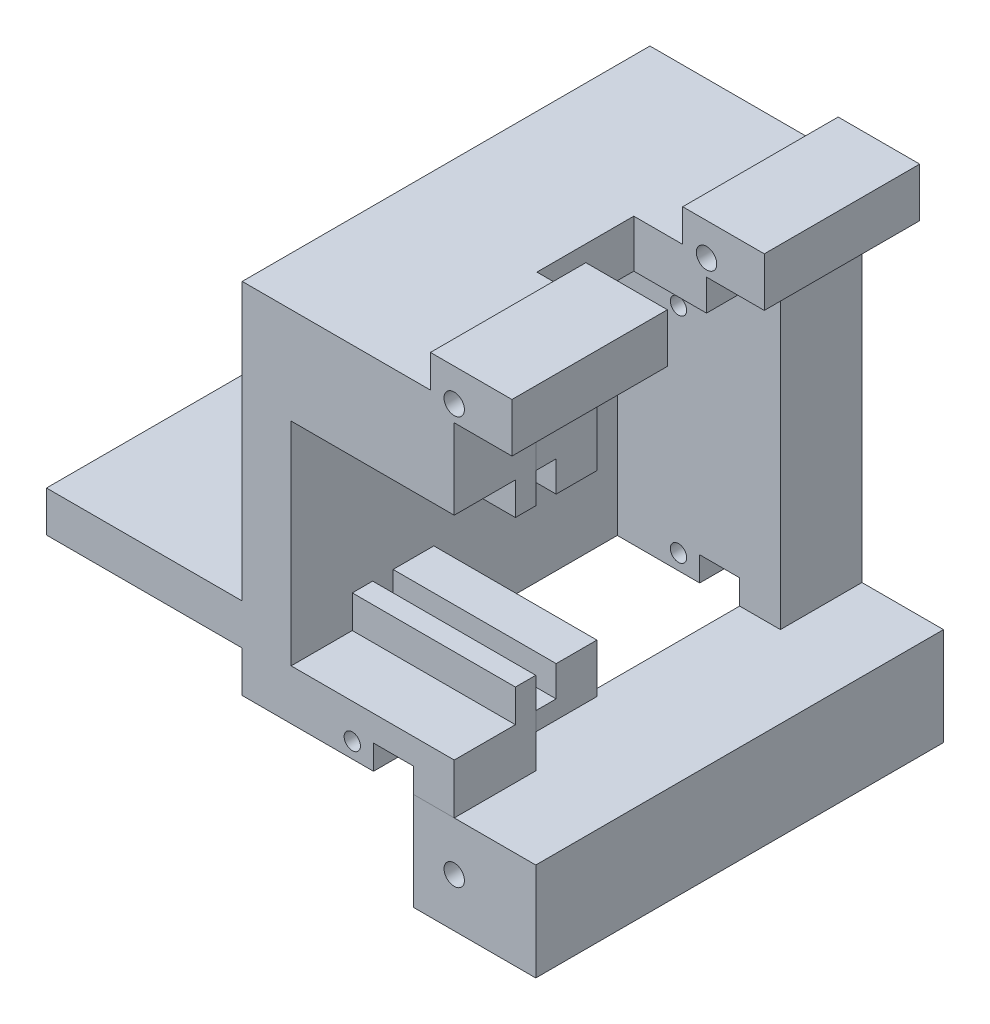
SolidWorks part; units mm, degrees
material "ABS"
ref_plane "Front Plane" through (0, 0, 0) normal (0, 0, 1) x (1, 0, 0)
ref_plane "Top Plane" through (0, 0, 0) normal (0, 1, 0) x (1, 0, 0)
ref_plane "Right Plane" through (0, 0, 0) normal (1, 0, 0) x (0, 0, -1)
sketch "Sketch8" plane through (0, 0, 0) normal (0, 0, 1) x (1, 0, 0)
  line L0 (0, 0) -> (0, 48.6918)
  line L1 (0, 48.6918) -> (-33.02, 48.6918)
  line L2 (-33.02, 48.6918) -> (-33.02, 5.588)
  line L3 (-33.02, 5.588) -> (-63.5, 5.588)
  line L4 (-63.5, 5.588) -> (-63.5, -0.762)
  line L5 (-63.5, -0.762) -> (-33.02, -0.762)
  line L6 (-33.02, -0.762) -> (-33.02, -9.525)
  line L8 (-33.02, -9.525) -> (-9.525, -9.525)
  line L11 (0, 0) -> (0, -9.525)
  line L12 (0, -9.525) -> (-9.525, -9.525)
  line L13 (-15.875, -4.7625) -> (-15.875, 28.5877) construction
  circle A0 centre (-15.875, 28.5877) radius 1.27
  circle A1 centre (-15.875, -4.7625) radius 1.27
  dimension "D7" = 2.54
  dimension "D8" = 15.875
  dimension "D1" = 30.48
  dimension "D2" = 33.02
  dimension "D3" = 48.6918
  dimension "D4" = 43.1038
  dimension "D5" = 6.35
  dimension "D6" = 23.495
extrude "Boss-Extrude3" add sketch "Sketch8" along normal blind 101.6
sketch "Sketch40" plane through (0, -9.525, 0) normal (0, -1, 0) x (1, 0, 0)
  line L0 (0, 0) -> (0, 31.75) construction
  line L1 (0, 101.6) -> (0, 0) construction
  line L2 (0, 31.75) -> (-25.4, 31.75)
  line L3 (-25.4, 31.75) -> (-25.4, 69.85)
  line L4 (-25.4, 69.85) -> (0, 69.85)
  line L5 (0, 69.85) -> (0, 31.75)
extrude "Cut-Extrude24" cut sketch "Sketch40" against normal blind 50.8
sketch "Sketch18" plane through (0, 0, 101.6) normal (0, 0, 1) x (1, 0, 0)
  line L0 (-33.02, -9.525) -> (-33.02, -7.1628)
  line L1 (-33.02, -0.762) -> (-33.02, -9.525) construction
  line L3 (-33.02, -7.1628) -> (0, -7.1628)
  line L4 (0, 48.6918) -> (0, -9.525) construction
  line L5 (0, -7.1628) -> (0, -9.525)
  line L6 (0, -9.525) -> (-33.02, -9.525)
extrude "Cut-Extrude11" cut sketch "Sketch18" against normal blind 101.6 and the other way through all
sketch "Sketch19" plane through (0, 0, 0) normal (0, 0, -1) x (-1, 0, 0)
  line L0 (3.7065, 48.6918) -> (3.7065, 53.7718)
  line L1 (0, 48.6918) -> (33.02, 48.6918) construction
  line L2 (3.7065, 53.7718) -> (-8.9935, 53.7718)
  line L3 (-8.9935, 53.7718) -> (-8.9935, 46.1359)
  line L6 (-8.9935, 46.1359) -> (0, 46.1359)
  circle A0 centre (15.875, -4.7625) radius 1.27 construction
  circle A1 centre (0, 48.6918) radius 1.5875
  point P0 (14.6053, -4.7356)
  point P1 (14.6053, -4.7894)
  point P4 (15.875, -4.7625)
  dimension "D1" = 3.175
  dimension "D2" = 5.08
sketch "Sketch20" plane through (0, 0, 101.6) normal (0, 0, 1) x (1, 0, 0)
  circle A0 centre (0, 48.6918) radius 1.5875
  dimension "D1" = 3.175
extrude "Boss-Extrude4" add sketch "Sketch19" against normal blind 101.6
extrude "Cut-Extrude12" cut sketch "Sketch20" against normal blind 101.6
sketch "Sketch21" plane through (0, -7.1628, 0) normal (0, -1, 0) x (1, 0, 0)
  line L28 (-33.02, 101.6) -> (0, 101.6)
  line L29 (0, 101.6) -> (0, 82.55)
  line L30 (0, 101.6) -> (0, 69.85) construction
  line L31 (0, 82.55) -> (-33.02, 82.55)
  line L32 (-33.02, 101.6) -> (-33.02, 0) construction
  line L33 (-33.02, 82.55) -> (-33.02, 101.6)
  line L34 (-33.02, 0) -> (-33.02, 19.05)
  line L35 (-33.02, 19.05) -> (0, 19.05)
  line L36 (0, 31.75) -> (0, 0) construction
  line L37 (0, 19.05) -> (0, 0)
  line L38 (0, 0) -> (-33.02, 0)
extrude "Cut-Extrude13" cut sketch "Sketch21" against normal through all
sketch "Sketch24" plane through (0, 53.7718, 0) normal (0, 1, 0) x (1, 0, 0)
  line L11 (8.9935, -101.6) -> (8.9935, 0) construction
  line L20 (0, -82.55) -> (8.9935, -82.55)
  line L21 (8.9935, -82.55) -> (8.9935, -101.6)
  line L22 (8.9935, -101.6) -> (0, -101.6)
  line L23 (0, -101.6) -> (0, -82.55)
  line L24 (0, 0) -> (8.9935, 0)
  line L25 (8.9935, 0) -> (8.9935, -19.05)
  line L26 (8.9935, -19.05) -> (0, -19.05)
  line L27 (0, -19.05) -> (0, 0)
extrude "Cut-Extrude15" cut sketch "Sketch24" against normal through all
sketch "Sketch38" plane through (8.9935, 0, 0) normal (1, 0, 0) x (0, 0, -1)
  line L10 (-50.8, 53.7718) -> (-43.2562, 53.7718) construction
  line L12 (-43.2562, 53.7718) -> (-58.3438, 53.7718)
  line L16 (-58.3438, 53.7718) -> (-58.3438, 46.1359)
  line L18 (-82.55, 46.1359) -> (-19.05, 46.1359) construction
  line L20 (-82.55, 53.7718) -> (-19.05, 53.7718) construction
  line L25 (-58.3438, 46.1359) -> (-43.2562, 46.1359)
  line L26 (-43.2562, 46.1359) -> (-43.2562, 53.7718)
extrude "Cut-Extrude21" cut sketch "Sketch38" against normal blind 20.32
sketch "Sketch41" plane through (0, 5.588, 0) normal (0, 1, 0) x (1, 0, 0)
  line L9 (-63.5, 0) -> (-33.02, 0)
  line L10 (-33.02, 0) -> (-33.02, -19.05)
  line L11 (-33.02, -19.05) -> (-33.02, 0) construction
  line L12 (-33.02, -19.05) -> (-63.5, -19.05)
  line L13 (-63.5, -101.6) -> (-63.5, 0) construction
  line L14 (-63.5, -19.05) -> (-63.5, 0)
  line L15 (-33.02, -101.6) -> (-63.5, -101.6)
  line L16 (-63.5, -101.6) -> (-63.5, -82.55)
  line L17 (-63.5, -82.55) -> (-33.02, -82.55)
  line L18 (-33.02, -82.55) -> (-33.02, -19.05) construction
  line L19 (-33.02, -101.6) -> (-33.02, -82.55) construction
  line L20 (-33.02, -82.55) -> (-33.02, -101.6)
extrude "Cut-Extrude25" cut sketch "Sketch41" against normal through all
sketch "Sketch42" plane through (0, 0, 69.85) normal (0, 0, -1) x (-1, 0, 0)
  line L0 (15.875, 28.5877) -> (15.875, 33.6677) construction
  line L1 (15.875, 33.6677) -> (0, 33.6677) construction
  line L2 (0, 41.275) -> (0, -7.1628) construction
sketch "Sketch43" plane through (0, 0, 0) normal (1, 0, 0) x (0, 0, -1)
  line L6 (-69.85, 33.6677) -> (-69.85, 0.6477)
  line L7 (-69.85, 41.275) -> (-69.85, -7.1628) construction
  line L8 (-69.85, 0.6477) -> (-82.55, 0.6477)
  line L9 (-82.55, 46.1359) -> (-82.55, -7.1628) construction
  line L10 (-82.55, 0.6477) -> (-82.55, 33.6677)
  line L11 (-82.55, 33.6677) -> (-69.85, 33.6677)
extrude "Cut-Extrude26" cut sketch "Sketch43" against normal blind 25.4
sketch "Sketch44" plane through (-25.4, 0, 0) normal (1, 0, 0) x (0, 0, -1)
  line L11 (-69.85, 33.6677) -> (-73.025, 33.6677)
  line L12 (-69.85, 33.6677) -> (-82.55, 33.6677) construction
  line L13 (-73.025, 33.6677) -> (-73.025, 28.5877)
  line L14 (-73.025, 28.5877) -> (-69.85, 28.5877)
  line L15 (-69.85, 0.6477) -> (-69.85, -7.1628) construction
  line L16 (-69.85, 28.5877) -> (-69.85, 33.6677)
  line L17 (-69.85, 0.6477) -> (-69.85, 5.7277)
  line L18 (-69.85, 5.7277) -> (-73.025, 5.7277)
  line L19 (-73.025, 5.7277) -> (-73.025, 0.6477)
  line L20 (-82.55, 0.6477) -> (-69.85, 0.6477) construction
  line L21 (-73.025, 0.6477) -> (-69.85, 0.6477)
extrude "Boss-Extrude5" add sketch "Sketch44" along normal blind 25.4
sketch "Sketch45" plane through (-25.4, 0, 0) normal (1, 0, 0) x (0, 0, -1)
  line L1 (-69.85, 41.275) -> (-31.75, 41.275) construction
  line L4 (-69.85, 41.275) -> (-69.85, 28.5877) construction
  line L7 (-60.325, 5.715) -> (-60.325, -1.905)
  line L8 (-60.325, -1.905) -> (-69.85, -1.905)
  line L14 (-60.325, 5.715) -> (-66.675, 5.715)
  line L15 (-66.675, 5.715) -> (-66.675, 0.9525)
  line L16 (-66.675, 0.9525) -> (-69.85, 0.9525)
  line L17 (-69.85, 0.9525) -> (-69.85, -1.905)
  line L19 (-31.75, -7.1628) -> (-69.85, -7.1628) construction
  line L21 (-69.85, 41.275) -> (-60.325, 41.275)
  line L22 (-60.325, 41.275) -> (-60.325, 28.575)
  line L24 (-69.85, 28.575) -> (-69.85, 41.275)
  line L25 (-60.325, 28.575) -> (-66.675, 28.575)
  line L26 (-66.675, 28.575) -> (-66.675, 33.3375)
  line L27 (-66.675, 33.3375) -> (-69.85, 33.3375)
  dimension "D3" = 5.2578
  dimension "D4" = 8.1153
  dimension "D5" = 12.8778
extrude "Boss-Extrude6" add sketch "Sketch45" along normal blind 25.4 separate body
sketch "Sketch46" plane through (0, 0, 82.55) normal (0, 0, 1) x (1, 0, 0)
  line L0 (0, 48.6918) -> (0, -14.8082) construction
  line L1 (0, -7.1628) -> (12.7, -7.1628)
  line L2 (12.7, -7.1628) -> (12.7, -22.4028)
  line L3 (12.7, -22.4028) -> (-6.35, -22.4028)
  line L4 (-6.35, -22.4028) -> (-6.35, -7.1628)
  line L6 (-33.02, -7.1628) -> (0, -7.1628) construction
  circle A0 centre (0, -14.8082) radius 1.5875
extrude "Boss-Extrude7" add sketch "Sketch46" against normal blind 63.5 separate body
sketch "Sketch48" plane through (0, 0, 82.55) normal (0, 0, 1) x (1, 0, 0)
  line L0 (-12.573, -7.1628) -> (-12.573, -3.3468)
  line L1 (-33.02, -7.1628) -> (0, -7.1628) construction
  line L2 (-12.573, -3.3468) -> (-6.35, -3.3468)
  line L3 (-6.35, -3.3468) -> (-6.35, -7.1628)
  circle A0 centre (-15.875, -4.7625) radius 1.27 construction
  dimension "D1" = 3.302
extrude "Cut-Extrude29" cut sketch "Sketch48" against normal blind 12.7 and the other way through all flip side to cut
sketch "Sketch49" plane through (0, 0, 19.05) normal (0, 0, -1) x (-1, 0, 0)
  line L0 (15.875, -4.7625) -> (12.573, -4.7625) construction
  line L1 (12.573, -7.1628) -> (12.573, -3.3528)
  line L2 (0, -7.1628) -> (33.02, -7.1628) construction
  line L3 (12.573, -3.3528) -> (6.35, -3.3528)
  line L4 (6.35, -3.3528) -> (6.35, -7.1628)
  line L5 (6.35, -7.1628) -> (12.573, -7.1628)
extrude "Cut-Extrude31" cut sketch "Sketch49" against normal blind 12.7
sketch "Sketch50" plane through (0, 46.1359, 0) normal (0, 1, 0) x (1, 0, 0)
  line L0 (0, -43.2562) -> (-11.3265, -43.2562)
  line L1 (-11.3265, -43.2562) -> (-11.3265, -58.3438)
  line L2 (-11.3265, -58.3438) -> (0, -58.3438)
  line L3 (0, -58.3438) -> (0, -43.2562)
extrude "Cut-Extrude33" cut sketch "Sketch50" against normal blind 4.8768
